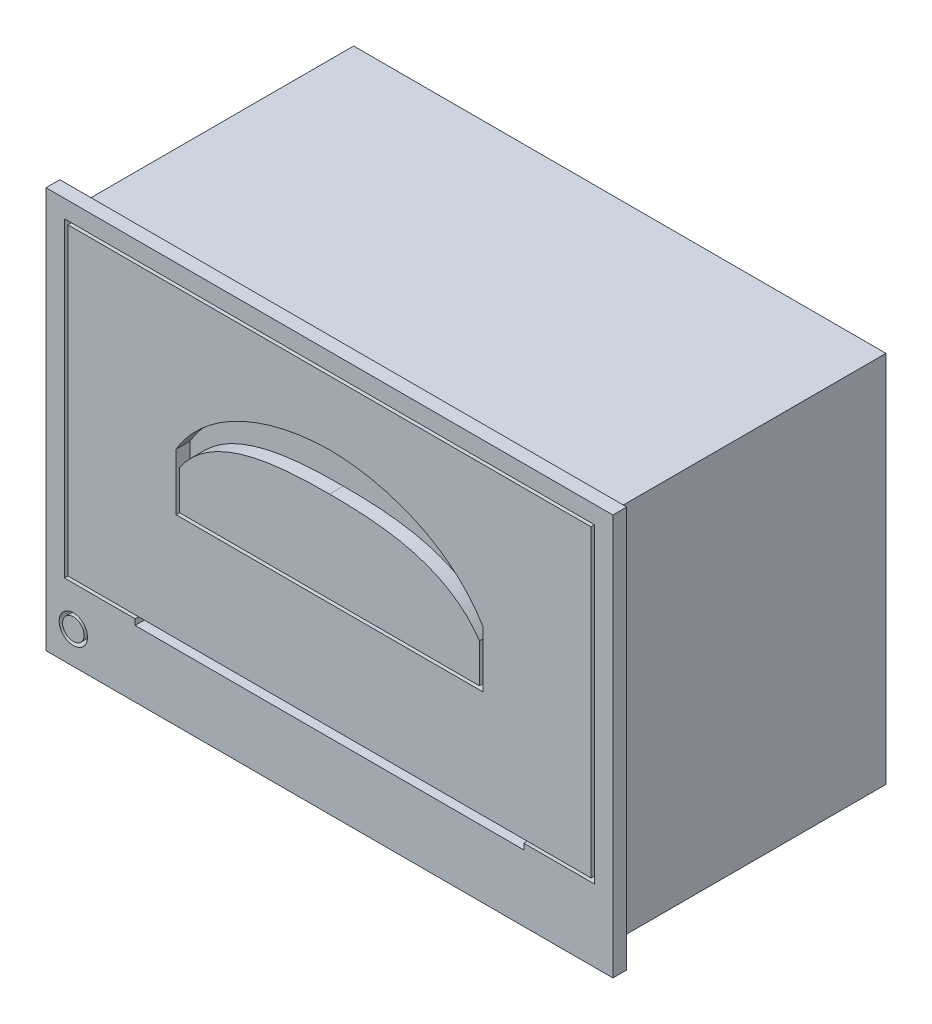
SolidWorks part; units mm, degrees
ref_plane "前视基准面" through (0, 0, 0) normal (0, 0, 1) x (1, 0, 0)
ref_plane "上视基准面" through (0, 0, 0) normal (0, 1, 0) x (1, 0, 0)
ref_plane "右视基准面" through (0, 0, 0) normal (1, 0, 0) x (0, 0, -1)
sketch "草图1" plane through (0, 0, 0) normal (0, 0, 1) x (1, 0, 0)
  line L0 (-94.1302, 0) -> (80.3018, 0) construction
  line L1 (-41, 29) -> (41, 29)
  line L2 (-41, 29) -> (-41, -29)
  line L3 (-41, -29) -> (41, -29)
  line L4 (41, 29) -> (41, -29)
  line L5 (0, 40.6361) -> (0, -45.4882) construction
  dimension "D1" = 82
  dimension "D2" = 58
extrude "凸台-拉伸1" add sketch "草图1" against normal blind 42
sketch "草图2" plane through (0, 0, -42) normal (0, 0, -1) x (-1, 0, 0)
  line L0 (0, 31.9735) -> (0, -31.889) construction
  line L1 (-38.5, 27) -> (38.5, 27)
  line L2 (-38.5, 27) -> (-38.5, -27)
  line L3 (-38.5, -27) -> (38.5, -27)
  line L4 (38.5, 27) -> (38.5, -27)
  line L5 (-51.7827, 0) -> (44.6869, 0) construction
  dimension "D1" = 77
  dimension "D2" = 54
extrude "切除-拉伸1" cut sketch "草图2" against normal offset from surface (40 mm away) 2 flip side to cut up to face at (0, 0, 0)
sketch "草图3" plane through (0, 0, 0) normal (0, 0, 1) x (1, 0, 0)
  line L0 (0, 33.8781) -> (0, -39.3235) construction
  line L1 (-37.8315, 25.9425) -> (37.8315, 25.9425)
  line L2 (-38.3315, 26.4425) -> (38.3315, 26.4425)
  line L3 (-38.3315, 26.4425) -> (-38.3315, -18.5553)
  line L4 (-38.3315, -18.5553) -> (38.3315, -18.5553)
  line L5 (38.3315, 26.4425) -> (38.3315, -18.5553)
  line L6 (37.8315, 25.9425) -> (37.8315, -18.0553)
  line L7 (-37.8315, -18.0553) -> (37.8315, -18.0553)
  line L8 (-37.8315, 25.9425) -> (-37.8315, -18.0553)
  circle A0 centre (-37.0495, -24.3243) radius 2.0512
  circle A1 centre (-37.0495, -24.3243) radius 1.5512
  dimension "D1" = 0.5
  dimension "D2" = 0.5
extrude "切除-拉伸2" cut sketch "草图3" against normal blind 2
sketch "草图5" plane through (0, 0, 0) normal (0, 0, 1) x (1, 0, 0)
  line L0 (0, 34.6088) -> (0, -41.0799) construction
  line L1 (-38.3315, -18.5553) -> (38.3315, -18.5553) construction
  line L2 (-28.1105, -18.5553) -> (28.1105, -18.5553)
  line L3 (-28.1105, -18.5553) -> (-28.1105, -19.3953)
  line L4 (-28.1105, -19.3953) -> (28.1105, -19.3953)
  line L5 (28.1105, -18.5553) -> (28.1105, -19.3953)
  line L6 (21.6936, -2.0568) -> (-21.6936, -2.0568)
  line L7 (-21.6936, -2.0568) -> (-21.6936, 3.5769)
  line L8 (21.6936, -2.0568) -> (21.6936, 3.5769)
  line L9 (22.1815, -2.5568) -> (-22.1815, -2.5568)
  line L10 (-22.1815, -2.5568) -> (-22.1815, 5.6653)
  line L11 (22.1815, -2.5568) -> (22.1815, 5.6653)
  spline S0 degree 3 poles (-21.6936, 3.5769) (-17.0483, 10.5048) (-7.4433, 11.1365) (0, 11.1223) knots 0 0 0 0 1 1 1 1
  spline S1 degree 3 poles (21.6936, 3.5769) (17.0483, 10.5048) (7.4433, 11.1365) (0, 11.1223) knots 0 0 0 0 1 1 1 1
  spline S4 degree 3 poles (-22.1815, 5.6653) (-21.6132, 6.595) (-20.3244, 8.3825) (-17.2437, 11.3858) (-12.6222, 14.2164) (-7.4233, 15.8683) (-3.1583, 16.5376) (-1.0572, 16.6609) (0, 16.6722) knots -0.005482 -0.005482 -0.005482 -0.005482 0.12023 0.245943 0.497368 0.748792 0.874505 1.000217 1.000217 1.000217 1.000217
  spline S5 degree 3 poles (0, 16.6722) (1.0572, 16.6609) (3.1583, 16.5376) (7.4233, 15.8683) (12.6222, 14.2164) (17.2437, 11.3858) (20.3244, 8.3825) (21.6132, 6.595) (22.1815, 5.6653) knots -0.005482 -0.005482 -0.005482 -0.005482 0.12023 0.245943 0.497368 0.748792 0.874505 1.000217 1.000217 1.000217 1.000217
  point P20 (0, -2.0568)
extrude "切除-拉伸3" cut sketch "草图5" against normal blind 2
